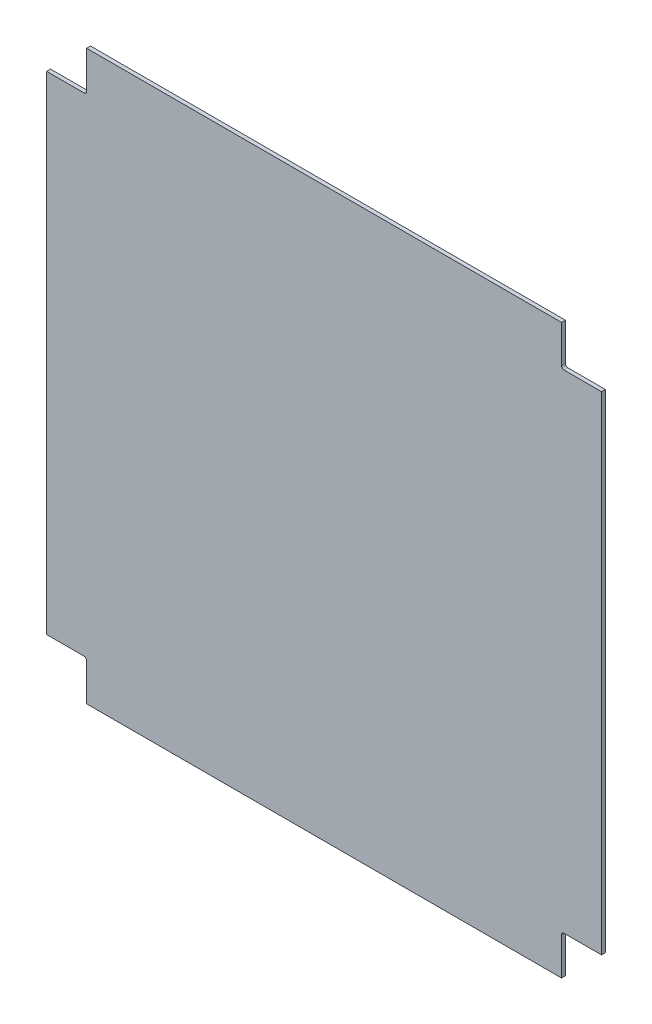
SolidWorks part; units mm, degrees
ref_plane "Front Plane" through (0, 0, 0) normal (0, 0, 1) x (1, 0, 0)
ref_plane "Top Plane" through (0, 0, 0) normal (0, 1, 0) x (1, 0, 0)
ref_plane "Right Plane" through (0, 0, 0) normal (1, 0, 0) x (0, 0, -1)
sketch "Sketch1" plane through (0, 0, 0) normal (0, 0, 1) x (1, 0, 0)
  line L0 (0, 427.6735) -> (0, 0) construction
  line L1 (0, 0) -> (427.6735, 0) construction
  line L2 (215, 189) -> (186, 189)
  line L3 (-215, 220) -> (215, 220)
  line L4 (-215, 220) -> (-215, -220)
  line L5 (-215, -220) -> (215, -220)
  line L6 (215, 220) -> (215, -220)
  line L7 (-215, 220) -> (-184, 220)
  line L8 (-215, 220) -> (-215, 189)
  line L9 (-215, 189) -> (-186, 189)
  line L10 (-184, 220) -> (-184, 191)
  line L11 (184, 220) -> (184, 191)
  line L12 (215, 220) -> (184, 220)
  line L13 (215, 220) -> (215, 189)
  line L14 (215, -220) -> (184, -220)
  line L15 (184, -220) -> (184, -191)
  line L16 (215, -189) -> (186, -189)
  line L17 (215, -220) -> (215, -189)
  line L18 (-215, -189) -> (-186, -189)
  line L19 (-184, -220) -> (-184, -191)
  line L20 (-215, -220) -> (-184, -220)
  line L21 (-215, -220) -> (-215, -189)
  arc A0 (-186, 189) -> (-184, 191) centre (-186, 191) ccw
  arc A1 (186, 189) -> (184, 191) centre (186, 191) cw
  arc A2 (186, -189) -> (184, -191) centre (186, -191) ccw
  arc A3 (-186, -189) -> (-184, -191) centre (-186, -191) cw
  point P13 (-184, 189)
  dimension "D5" = 2
  dimension "D1" = 440
  dimension "D2" = 430
  dimension "D3" = 31
  dimension "D4" = 31
extrude "Boss-Extrude1" add sketch "Sketch1" along normal blind 3 contours L18 A3 L19 L5 L15 A2 L16 L6 L2 A1 L11 L3 L10 A0 L9 L4
